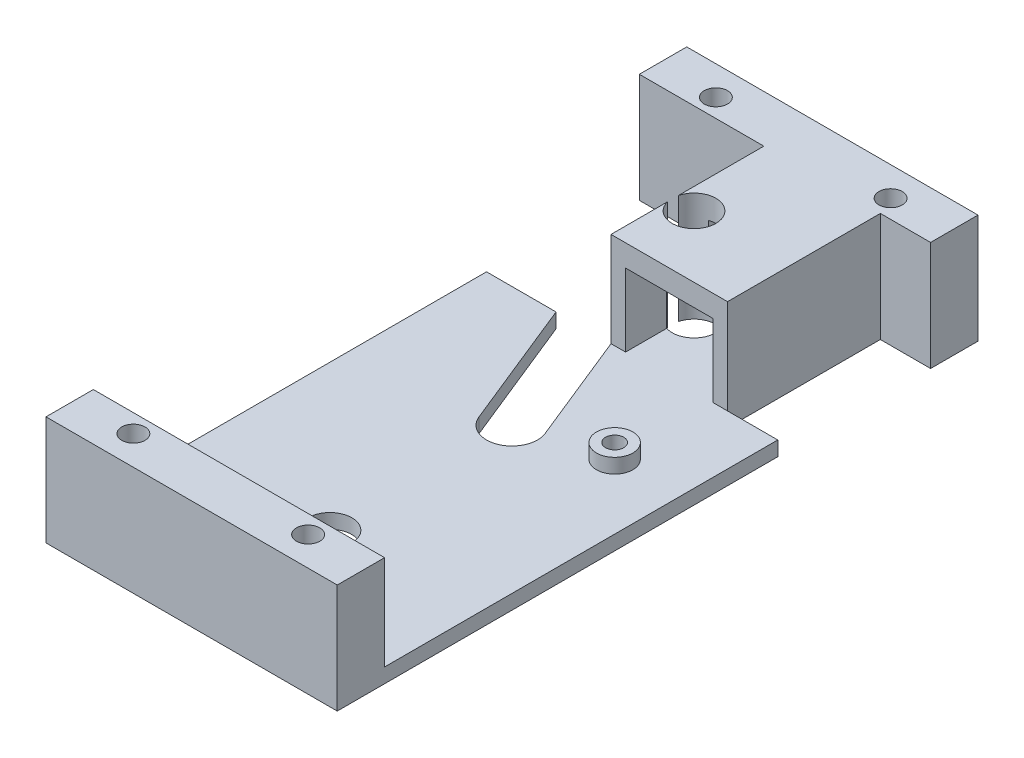
SolidWorks part; units mm, degrees
ref_plane "Alzado" through (0, 0, 0) normal (0, 0, 1) x (1, 0, 0)
ref_plane "Planta" through (0, 0, 0) normal (0, 1, 0) x (1, 0, 0)
ref_plane "Vista lateral" through (0, 0, 0) normal (1, 0, 0) x (0, 0, -1)
sketch "Croquis1" plane through (0, 0, 0) normal (0, 1, 0) x (1, 0, 0)
  line L0 (0, 0) -> (0, 50000) construction
  line L1 (-20, 44) -> (20, 44)
  line L2 (-20, 44) -> (-20, -44)
  line L3 (-20, -44) -> (20, -44)
  line L4 (20, 44) -> (20, -44)
  line L5 (-20, 44) -> (20, -44) construction
  line L6 (-20, -44) -> (20, 44) construction
  line L7 (0, 0) -> (50000, 0) construction
  circle A0 centre (-12, 40) radius 1.6
  circle A1 centre (12, 40) radius 1.6
  circle A2 centre (-12, -40) radius 1.6
  circle A3 centre (12, -40) radius 1.6
  point P0 (0, 0)
  dimension "D4" = 3.2
  dimension "D1" = 40
  dimension "D2" = 88
  dimension "D3" = 24
  dimension "D5" = 4
extrude "Saliente-Extruir1" add sketch "Croquis1" along normal blind 15
sketch "Croquis2" plane through (0, 15, 0) normal (0, 1, 0) x (1, 0, 0)
  line L0 (0, 0) -> (0, 50000) construction
  line L1 (-19.1, 16.5) -> (19.1, 16.5) construction
  line L2 (-19.1, 16.5) -> (-19.1, -37.5) construction
  line L3 (-19.1, -37.5) -> (19.1, -37.5) construction
  line L4 (19.1, 16.5) -> (19.1, -37.5) construction
  line L5 (-19.1, 16.5) -> (19.1, -37.5) construction
  line L6 (-19.1, -37.5) -> (19.1, 16.5) construction
  line L7 (-0.9, 48.3966) -> (11.1, 48.3966)
  line L8 (-0.9, 48.3966) -> (-0.9, 16.5)
  line L9 (-0.9, 16.5) -> (11.1, 16.5) construction
  line L10 (11.1, 48.3966) -> (11.1, 16.5)
  line L11 (-0.9, 48.3966) -> (11.1, 16.5) construction
  line L12 (-0.9, 16.5) -> (11.1, 48.3966) construction
  line L13 (0, 0) -> (50000, 0) construction
  line L14 (-20, 44) -> (-20, -44) construction
  line L15 (-20, 16.5) -> (20, 16.5) construction
  line L16 (-20, 16.5) -> (-20, -37.5)
  line L17 (-20, -37.5) -> (20, -37.5)
  line L18 (20, 16.5) -> (20, -37.5)
  line L19 (-20, 16.5) -> (20, -37.5) construction
  line L20 (-20, -37.5) -> (20, 16.5) construction
  line L21 (20, -44) -> (20, 44) construction
  line L22 (-20, 16.5) -> (-0.9, 16.5)
  line L23 (11.1, 16.5) -> (20, 16.5)
  circle A0 centre (12, -40) radius 1.6 construction
  circle A2 centre (11.1, 3) radius 1.25 construction
  circle A3 centre (4.1, -34.5) radius 1.25 construction
  point P0 (0, -10.5)
  point P6 (5.1, 32.4483)
  point P21 (0, -10.5)
  dimension "D5" = 2.5
  dimension "D7" = 13.5
  dimension "D10" = 2.5
  dimension "D1" = 54
  dimension "D2" = 38.2
  dimension "D3" = 14
  dimension "D4" = 12
  dimension "D6" = 8
  dimension "D8" = 3
  dimension "D9" = 15
extrude "Cortar-Extruir1" cut sketch "Croquis2" against normal offset from surface (13 mm away) 2 up to face at (0, 0, 0)
sketch "Croquis3" plane through (0, 2, 0) normal (0, 1, 0) x (1, 0, 0)
  circle A0 centre (11.1, 3) radius 2.5
  circle A1 centre (4.1, -34.5) radius 2.5
  dimension "D1" = 5
extrude "Saliente-Extruir3" add sketch "Croquis3" along normal blind 2
sketch "Croquis4" plane through (0, 4, 0) normal (0, 1, 0) x (1, 0, 0)
  circle A0 centre (11.1, 3) radius 1.25
  circle A1 centre (4.1, -34.5) radius 1.25
extrude "Cortar-Extruir2" cut sketch "Croquis4" against normal through all
sketch "Croquis5" plane through (0, 15, 0) normal (0, 1, 0) x (1, 0, 0)
  line L0 (-20, 44) -> (-20, 16.5) construction
  line L1 (-2.9, 16.5) -> (-20, 16.5)
  line L2 (-2.9, 16.5) -> (-2.9, 37.4886)
  line L3 (-2.9, 37.4886) -> (-20, 37.4886)
  line L4 (-20, 16.5) -> (-20, 37.4886)
  line L5 (-2.9, 16.5) -> (-20, 37.4886) construction
  line L6 (-2.9, 37.4886) -> (-20, 16.5) construction
  line L7 (20, 16.5) -> (20, 44) construction
  line L8 (20, 37.4886) -> (13.1, 37.4886)
  line L9 (20, 37.4886) -> (20, 16.5)
  line L10 (20, 16.5) -> (13.1, 16.5)
  line L11 (13.1, 37.4886) -> (13.1, 16.5)
  line L12 (20, 37.4886) -> (13.1, 16.5) construction
  line L13 (20, 16.5) -> (13.1, 37.4886) construction
  line L14 (-0.9, 48.3966) -> (-0.9, 16.5) construction
  line L15 (11.1, 48.3966) -> (11.1, 16.5) construction
  line L16 (-20, 16.5) -> (-0.9, 16.5) construction
  line L17 (11.1, 16.5) -> (20, 16.5) construction
  point P4 (-11.45, 26.9943)
  point P11 (16.55, 26.9943)
  dimension "D1" = 2
  dimension "D2" = 2
extrude "Cortar-Extruir3" cut sketch "Croquis5" against normal through all
sketch "Croquis6" plane through (0, 15, 0) normal (0, 1, 0) x (1, 0, 0)
  line L0 (11.1, 44) -> (11.1, 41.3229)
  line L1 (-0.9, 44) -> (11.1, 44)
  line L2 (-0.9, 44) -> (-0.9, 16.5)
  line L3 (-0.9, 16.5) -> (11.1, 16.5)
  line L4 (11.1, 44) -> (11.1, 16.5) construction
  line L5 (-0.9, 44) -> (11.1, 16.5) construction
  line L6 (-0.9, 16.5) -> (11.1, 44) construction
  line L7 (11.1, 38.6771) -> (11.1, 16.5)
  arc A0 (11.1, 41.3229) -> (11.1, 38.6771) centre (12, 40) ccw
  arc A1 (11.1, 38.6771) -> (11.1, 41.3229) centre (12, 40) ccw construction
  point P4 (5.1, 30.25)
extrude "Saliente-Extruir4" add sketch "Croquis6" against normal offset from surface (3 mm away) 8 up to face at (11.1, 4, -1.75)
sketch "Croquis7" plane through (0, 0, -44) normal (0, 0, -1) x (-1, 0, 0)
  line L0 (-18.385, 9.3531) -> (-13.0548, 9.3531)
  line L1 (-13.0548, 9.3531) -> (-13.0548, 8.6452)
  line L2 (-13.0548, 8.6452) -> (-13.5962, 7.8123)
  line L3 (-13.5962, 7.8123) -> (-17.8437, 7.8123)
  line L4 (-17.8437, 7.8123) -> (-18.385, 8.6452)
  line L5 (-18.385, 8.6452) -> (-18.385, 9.3531)
  point P2 (-15.7199, 7.8123)
  point P7 (-15.7199, 9.3531)
extrude "Cortar-Extruir4" cut sketch "Croquis7" against normal blind 1
sketch "Croquis8" plane through (0, 0, 0) normal (0, -1, 0) x (1, 0, 0)
  line L0 (0, 200000) -> (0, -250000) construction
  line L1 (-200000, 0) -> (250000, 0) construction
  line L2 (0, 0) -> (49742.9222, 0) construction
  line L3 (-2.9, -16.5) -> (3.2441, -1.3124)
  line L4 (3.2441, -1.3124) -> (-3.2441, 1.3124) construction
  line L5 (-3.2441, 1.3124) -> (-10.45, -16.5)
  line L6 (-20, -16.5) -> (-0.9, -16.5) construction
  line L7 (-10.45, -16.5) -> (-2.9, -16.5)
  circle A0 centre (0, 25) radius 3
  circle A1 centre (0, -25) radius 3
  circle A2 centre (0, 0) radius 4 construction
  arc A3 (-3.2441, 1.3124) -> (3.2441, -1.3124) centre (0, 0) cw
  point P21 (0, 0)
  dimension "D1" = 6
  dimension "D3" = 8
  dimension "D2" = 25
extrude "Cortar-Extruir5" cut sketch "Croquis8" against normal through all
